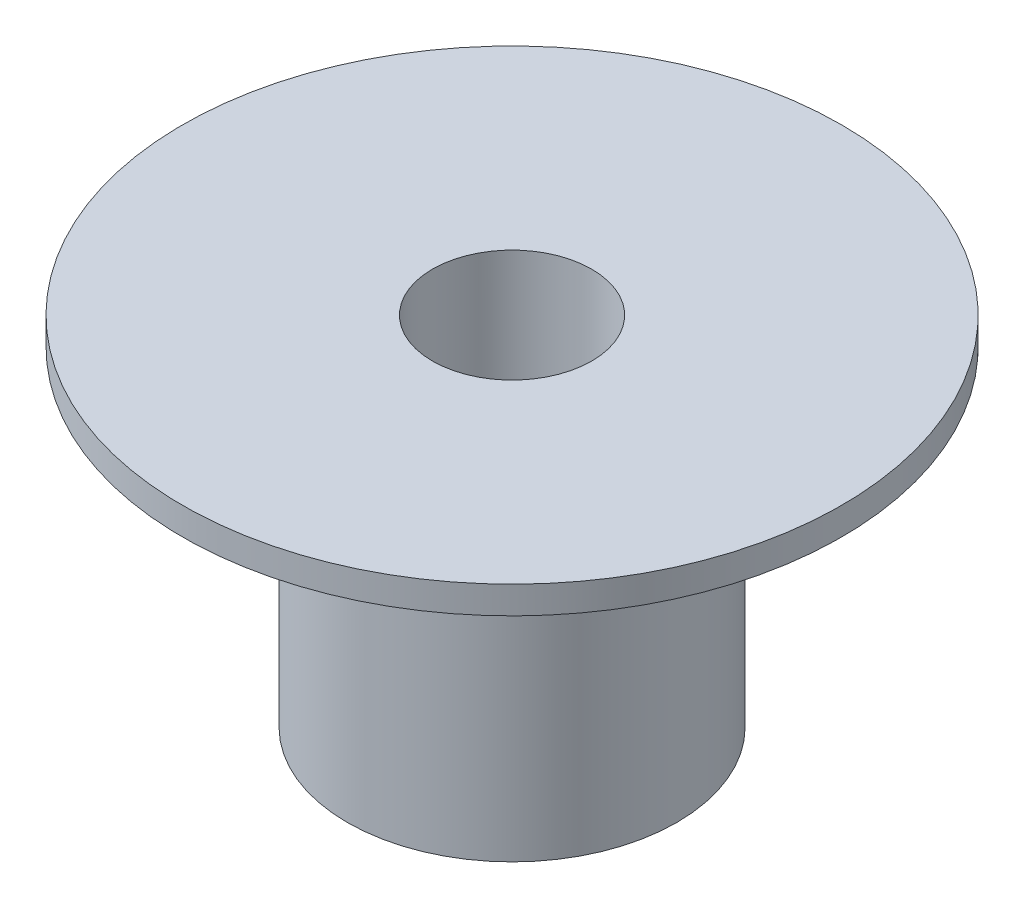
SolidWorks part; units mm, degrees
ref_plane "Front Plane" through (0, 0, 0) normal (0, 0, 1) x (1, 0, 0)
ref_plane "Top Plane" through (0, 0, 0) normal (0, 1, 0) x (1, 0, 0)
ref_plane "Right Plane" through (0, 0, 0) normal (1, 0, 0) x (0, 0, -1)
sketch "Sketch1" plane through (0, 0, 0) normal (1, 0, 0) x (0, 0, -1)
  line L0 (0, 0) -> (6, 0)
  line L1 (6, 0) -> (6, -0.5)
  line L2 (6, -0.5) -> (3, -0.5)
  line L3 (3, -0.5) -> (3, -6.5)
  line L4 (3, -6.5) -> (0, -6.5)
  line L5 (0, -6.5) -> (0, 0)
  dimension "D1" = 0.5
  dimension "D2" = 6
  dimension "D3" = 3
  dimension "D4" = 6
revolve "Revolve1" add sketch "Sketch1" angle 360 about L5
hole_wizard "M3.5x0.6 Tapped Hole1" positions "Sketch3" profile "Sketch2" tap size "M3.5x0.6" standard "Ansi Metric" end condition up to next
sketch "Sketch3" plane through (0, -6.5, 0) normal (0, -1, 0) x (1, 0, 0)
  point P0 (0, 0)
sketch "Sketch2" plane through (0, -6.5, 0) normal (1, 0, 0) x (0, 0, -1)
  line L0 (0, 0) -> (0, 6.5)
  line L1 (0, 6.5) -> (1.45, 6.5)
  line L2 (1.45, 6.5) -> (1.45, 0)
  line L5 (1.45, 0) -> (0, 0)
  line L11 (0, -6.35) -> (0, 107.95) construction
  dimension "Thru Tap Drill Dia." = 2.9
  dimension "Thru Tap Drill Depth" = 6.5
cosmetic thread "Hole Thread1"
